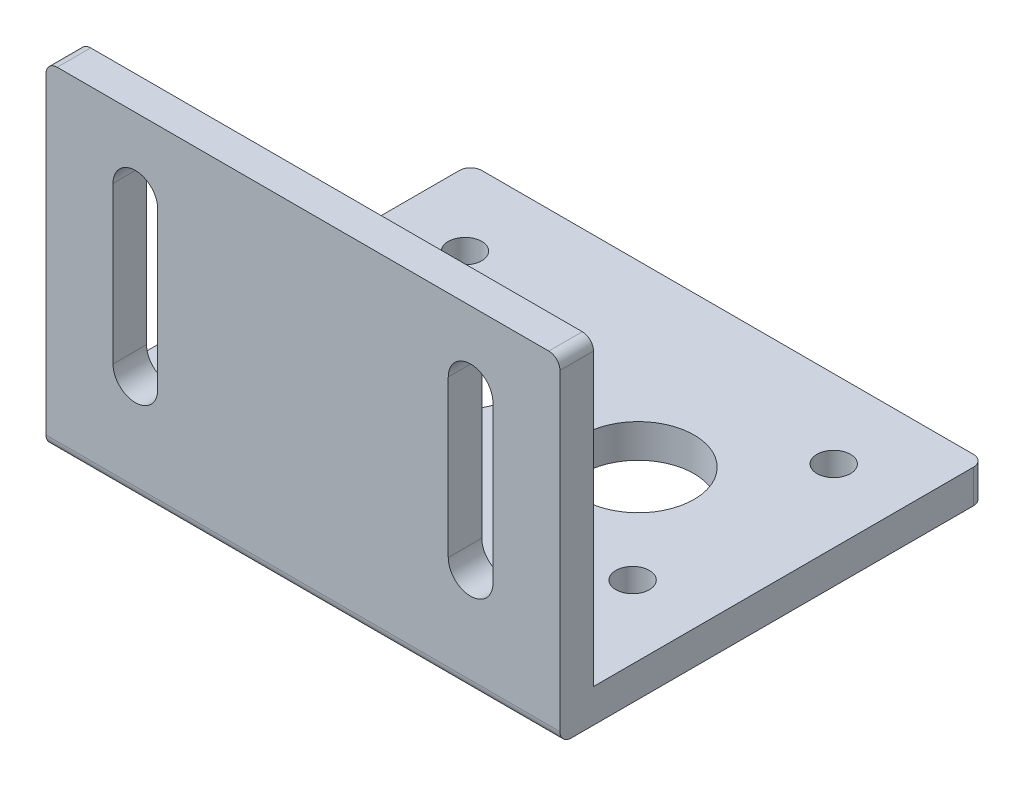
SolidWorks part; units mm, degrees
ref_plane "Front Plane" through (0, 0, 0) normal (0, 0, 1) x (1, 0, 0)
ref_plane "Top Plane" through (0, 0, 0) normal (0, 1, 0) x (1, 0, 0)
ref_plane "Right Plane" through (0, 0, 0) normal (1, 0, 0) x (0, 0, -1)
sketch "Sketch2" plane through (0, 0, 0) normal (0, 1, 0) x (1, 0, 0)
  line L0 (8, 19) -> (8, 3) construction
  line L1 (-22, 19) -> (22, 19)
  line L2 (-23, 18) -> (-23, -19)
  line L3 (-23, -19) -> (23, -19)
  line L4 (23, 18) -> (23, -19)
  line L5 (-23, 19) -> (23, -19) construction
  line L6 (-23, -19) -> (23, 19) construction
  line L7 (8, 3) -> (23, 3) construction
  line L8 (0, 19) -> (0, -19) construction
  line L9 (-23, 3) -> (23, 3) construction
  circle A0 centre (8, 3) radius 5
  circle A1 centre (-8, 3) radius 5
  circle A2 centre (-16.5, 12) radius 1.5
  circle A3 centre (-16.5, -6) radius 1.5
  circle A4 centre (16.5, -6) radius 1.5
  circle A5 centre (16.5, 12) radius 1.5
  arc A6 (23, 18) -> (22, 19) centre (22, 18) ccw
  arc A7 (-22, 19) -> (-23, 18) centre (-22, 18) ccw
  point P0 (0, 0)
  point P29 (0, 0)
  dimension "D5" = 16.5
  dimension "D7" = 1
  dimension "D1" = 46
  dimension "D2" = 38
  dimension "D3" = 16
  dimension "D4" = 15
  dimension "D6" = 9
extrude "Boss-Extrude1" add sketch "Sketch2" along normal blind 3
sketch "Sketch3" plane through (0, 3, 0) normal (0, 1, 0) x (1, 0, 0)
  line L0 (0, 19) -> (0, -19) construction
  line L1 (22, 19) -> (-22, 19) construction
  line L2 (-23, -19) -> (23, -19) construction
  line L3 (23, -19) -> (23, 18) construction
  line L4 (-23, -19) -> (23, -19)
  line L5 (-23, -19) -> (-23, -16)
  line L6 (-23, -16) -> (23, -16)
  line L7 (23, -19) -> (23, -16)
  dimension "3" = 3
extrude "Boss-Extrude2" add sketch "Sketch3" along normal blind 27
sketch "Sketch4" plane through (0, 0, 16) normal (0, 0, -1) x (-1, 0, 0)
  line L0 (0, 30) -> (0, 3) construction
  line L1 (-23, 30) -> (23, 30) construction
  line L2 (-22, 3) -> (22, 3) construction
  line L3 (-23, 23.5) -> (23, 23.5) construction
  line L4 (-23, 30) -> (-23, 3) construction
  line L5 (23, 30) -> (23, 3) construction
  line L6 (-15, 30) -> (-15, 3) construction
  line L7 (-17, 23.5) -> (-17, 9.5)
  line L8 (-13, 23.5) -> (-13, 9.5)
  line L9 (13, 23.5) -> (13, 9.5)
  line L10 (17, 23.5) -> (17, 9.5)
  arc A2 (-13, 23.5) -> (-17, 23.5) centre (-15, 23.5) ccw
  arc A3 (-13, 9.5) -> (-17, 9.5) centre (-15, 9.5) cw
  arc A4 (13, 23.5) -> (17, 23.5) centre (15, 23.5) cw
  arc A5 (13, 9.5) -> (17, 9.5) centre (15, 9.5) ccw
  dimension "D1" = 6.5
  dimension "D2" = 15
extrude "Cut-Extrude1" cut sketch "Sketch4" against normal through all
fillet "Fillet1" radius 1 2 edges at (-23, 30, 17.5) (23, 30, 17.5)
fillet "Fillet2" radius 1 1 edges at (0, 0, 19)
